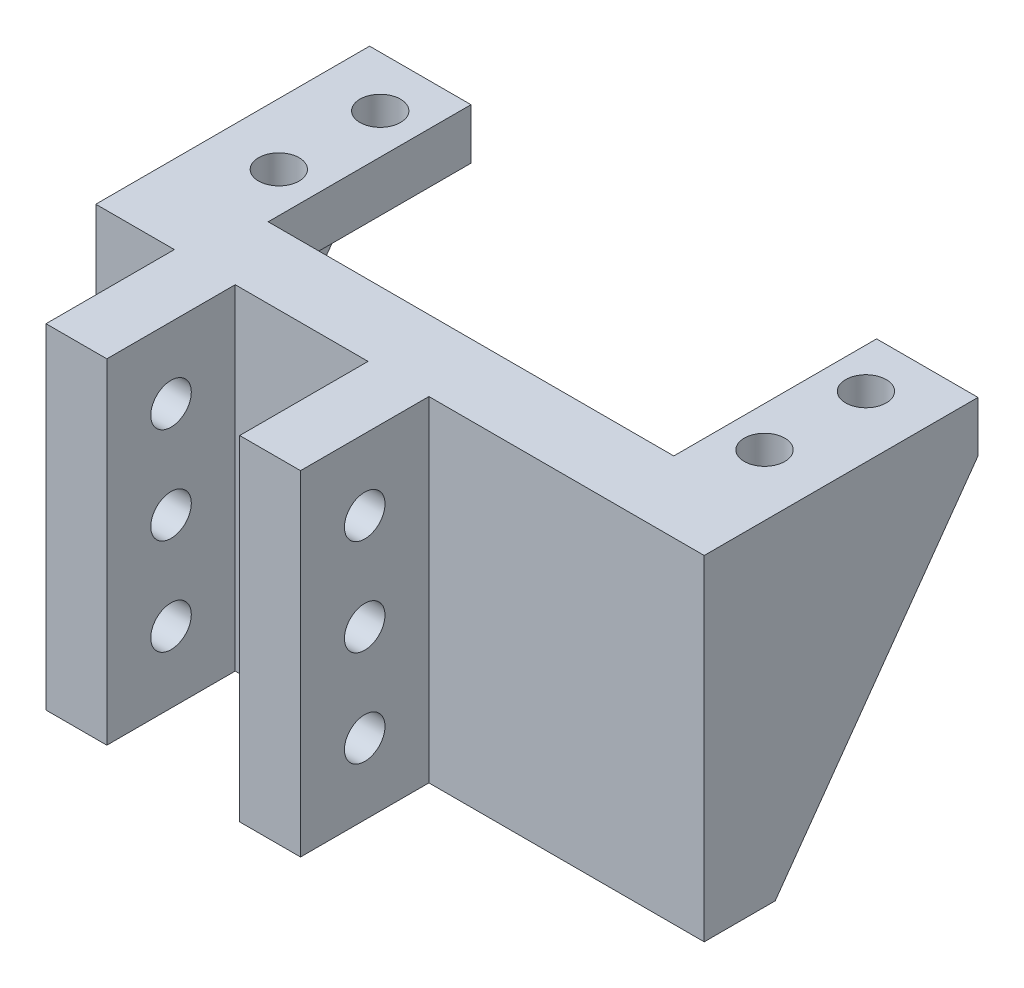
SolidWorks part; units mm, degrees
ref_plane "Front Plane" through (0, 0, 0) normal (0, 0, 1) x (1, 0, 0)
ref_plane "Top Plane" through (0, 0, 0) normal (0, 1, 0) x (1, 0, 0)
ref_plane "Right Plane" through (0, 0, 0) normal (1, 0, 0) x (0, 0, -1)
sketch "Sketch2" plane through (0, 0, 0) normal (0, 1, 0) x (1, 0, 0)
  line L1 (0, 0) -> (40, 0) construction
  line L2 (0, 0) -> (0, 20) construction
  line L3 (0, 20) -> (40, 20) construction
  line L4 (40, 0) -> (40, 20) construction
  line L5 (0, 20) -> (-8, 20)
  line L6 (0, 20) -> (0, 0)
  line L7 (0, 0) -> (-8, 0)
  line L8 (-8, 20) -> (-8, 0)
  line L9 (40, 0) -> (48, 0)
  line L10 (40, 0) -> (40, 20)
  line L11 (40, 20) -> (48, 20)
  line L12 (48, 0) -> (48, 20)
  line L13 (-8, 0) -> (48, 0)
  line L14 (-8, 0) -> (-8, -7)
  line L15 (-8, -7) -> (48, -7)
  line L16 (48, 0) -> (48, -7)
  line L17 (0, 0) -> (40, 0) construction
  line L18 (0, 0) -> (0, 20) construction
  line L19 (0, 20) -> (40, 20) construction
  line L20 (40, 0) -> (40, 20) construction
  line L21 (0, 0) -> (40, 20) construction
  line L22 (0, 20) -> (40, 0) construction
  line L23 (-8, -7) -> (3.75, -7)
  line L24 (-8, -7) -> (-8, -19.66)
  line L25 (-8, -19.66) -> (3.75, -19.66)
  line L26 (3.75, -7) -> (3.75, -19.66)
  line L27 (16.85, -7) -> (28.6, -7)
  line L28 (16.85, -7) -> (16.85, -19.66)
  line L29 (16.85, -19.66) -> (28.6, -19.66)
  line L30 (28.6, -7) -> (28.6, -19.66)
  point P8 (20, 10)
  point P21 (3.75, -19.6986)
  dimension "D1" = 8
  dimension "D2" = 20
  dimension "D3" = 40
  dimension "D4" = 12.66
  dimension "D5" = 3.75
  dimension "D6" = 13.1
  dimension "D7" = 7
  dimension "D8" = 11.75
extrude "Boss-Extrude1" add sketch "Sketch2" along normal blind 5 contours L5 L8 L7 L6 | L16 L9 L13 L7 L14 L15 | L26 L15 L24 L25 | L30 L15 L28 L29 | L9 L12 L11 L10
sketch "Sketch3" plane through (0, 0, 0) normal (0, -1, 0) x (1, 0, 0)
  line L0 (0, 0) -> (40, 0) construction
  line L1 (-8, 19.66) -> (3.75, 19.66)
  line L2 (-8, 19.66) -> (-8, 0)
  line L3 (-8, 0) -> (3.75, 0)
  line L4 (3.75, 19.66) -> (3.75, 0)
  line L5 (28.6, 7) -> (28.6, 19.66) construction
  line L6 (16.85, 19.66) -> (28.6, 19.66)
  line L7 (16.85, 19.66) -> (16.85, 0)
  line L8 (16.85, 0) -> (28.6, 0)
  line L9 (28.6, 19.66) -> (28.6, 0)
  line L11 (3.75, 0) -> (16.85, 0)
  line L12 (3.75, 0) -> (3.75, 7)
  line L13 (3.75, 7) -> (16.85, 7)
  line L14 (16.85, 0) -> (16.85, 7)
  line M15 (0, 0) -> (40, 0)
  line M20 (28.6, 7) -> (28.6, 19.66)
  line M21 (28.6, 19.66) -> (16.85, 19.66)
  line M22 (16.85, 19.66) -> (16.85, 7)
  line M23 (16.85, 7) -> (3.75, 7)
  line M24 (3.75, 7) -> (3.75, 19.66)
  line M25 (3.75, 19.66) -> (-8, 19.66)
  line M26 (-8, 19.66) -> (-8, -20)
extrude "Boss-Extrude2" add sketch "Sketch3" along normal blind 28 contours L4 L3 M24 M25 M26 M15 | L7 L4 M23 M15 | L9 L7 M20 M21 M22 M15
sketch "Sketch4" plane through (0, -28, 0) normal (0, -1, 0) x (1, 0, 0)
  line L1 (-8, 19.66) -> (-2.25, 19.66)
  line L2 (-8, 19.66) -> (-8, 7)
  line L3 (-8, 7) -> (-2.25, 7)
  line L4 (-2.25, 19.66) -> (-2.25, 7)
  line L5 (28.6, 19.66) -> (22.85, 19.66)
  line L6 (28.6, 19.66) -> (28.6, 7)
  line L7 (28.6, 7) -> (22.85, 7)
  line L8 (22.85, 19.66) -> (22.85, 7)
  line L9 (3.75, 19.66) -> (3.75, 7) construction
  line L10 (16.85, 19.66) -> (16.85, 7) construction
  line L11 (16.85, 7) -> (3.75, 7) construction
  dimension "D1" = 6
  dimension "D2" = 6
extrude "Cut-Extrude1" cut sketch "Sketch4" against normal through all
sketch "Sketch5" plane through (-2.25, 0, 0) normal (-1, 0, 0) x (0, 0, 1)
  line L0 (13.33, 5) -> (13.33, -28) construction
  line L1 (7, 5) -> (19.66, 5) construction
  line L2 (7, -28) -> (19.66, -28) construction
  circle A0 centre (13.33, -2) radius 2
  circle A1 centre (13.33, -21) radius 2
  circle A2 centre (13.33, -11.5) radius 2
  dimension "D1" = 4
  dimension "D2" = 7
  dimension "D3" = 7
extrude "Cut-Extrude2" cut sketch "Sketch5" against normal through all
sketch "Sketch6" plane through (0, 0, 0) normal (0, -1, 0) x (1, 0, 0)
  line L0 (40, -10) -> (0, -10) construction
  line L1 (-3.95, -5) -> (43.95, -5) construction
  line L2 (-3.95, -5) -> (-3.95, -15) construction
  line L3 (-3.95, -15) -> (43.95, -15) construction
  line L4 (43.95, -5) -> (43.95, -15) construction
  line L5 (40, 0) -> (40, -20) construction
  line L6 (0, -20) -> (0, 0) construction
  line L7 (20, -10) -> (20, -15) construction
  line L8 (20, -10) -> (20, -5) construction
  circle A0 centre (43.95, -5) radius 2
  circle A1 centre (43.95, -15) radius 2
  circle A2 centre (-3.95, -5) radius 2
  circle A3 centre (-3.95, -15) radius 2
  dimension "D3" = 4
  dimension "D1" = 10
  dimension "D2" = 47.9
extrude "Cut-Extrude3" cut sketch "Sketch6" against normal through all contours A2
sketch "Sketch7" plane through (28.6, 0, 0) normal (1, 0, 0) x (0, 0, -1)
  line L4 (-7, 0) -> (-7, -28)
  line L5 (-7, -28) -> (0, -28)
  line L6 (0, -28) -> (0, 0)
  line L7 (0, 0) -> (-7, 0)
  line L8 (-7, 0) -> (-7, -28)
  line L9 (-7, -28) -> (0, -28)
  line L10 (0, -28) -> (0, 0)
  line L11 (0, 0) -> (-7, 0)
  dimension "D1" = 0
extrude "Boss-Extrude3" add sketch "Sketch7" along normal up to surface (19.4 mm away) up to face at (48, 2.5, -6.5)
sketch "Sketch8" plane through (48, 0, 0) normal (1, 0, 0) x (0, 0, -1)
  line L1 (-7, -28) -> (20, -28)
  line L2 (-7, -28) -> (-7, 5)
  line L3 (-7, 5) -> (20, 5)
  line L4 (20, -28) -> (20, 5)
extrude "Boss-Extrude4" add sketch "Sketch8" along normal blind 2
sketch "Sketch9" plane through (-8, 0, 0) normal (-1, 0, 0) x (0, 0, 1)
  line L1 (-20, 5) -> (7, 5)
  line L2 (-20, 5) -> (-20, -28)
  line L3 (-20, -28) -> (7, -28)
  line L4 (7, 5) -> (7, -28)
extrude "Boss-Extrude5" add sketch "Sketch9" along normal blind 2
sketch "Sketch10" plane through (48, 0, 0) normal (-1, 0, 0) x (0, 0, 1)
  line L0 (-20, 0) -> (0, -28)
  line L1 (0, -28) -> (-20, -28)
  line L2 (-20, -28) -> (-20, 0)
extrude "Cut-Extrude4" cut sketch "Sketch10" against normal through all and the other way through all
